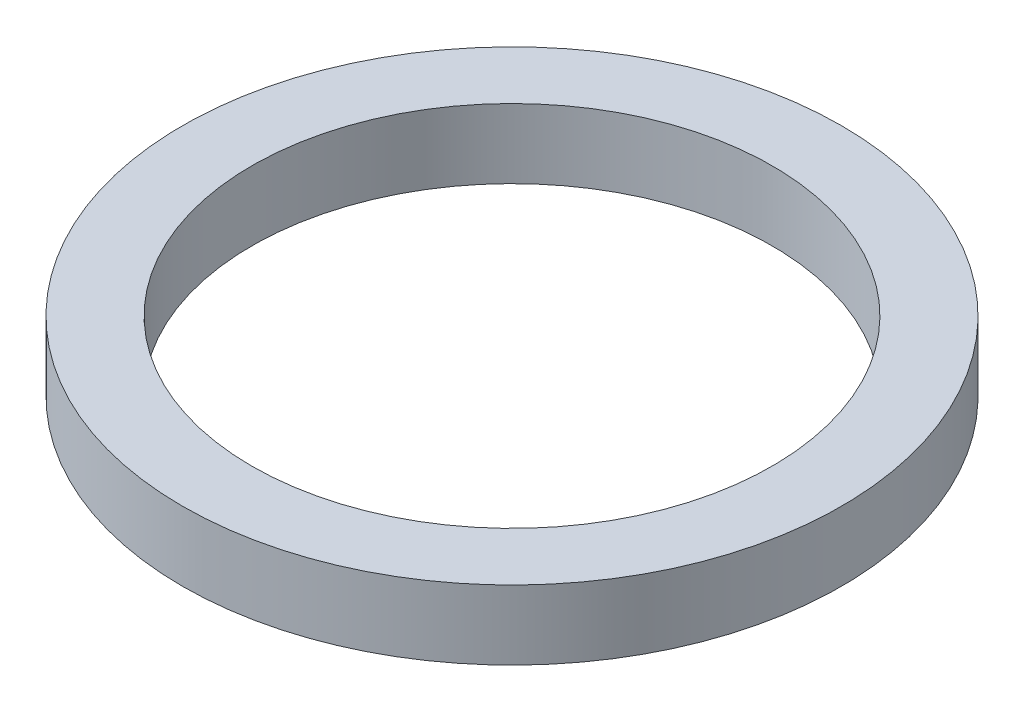
SolidWorks part; units mm, degrees
ref_plane "Front Plane" through (0, 0, 0) normal (0, 0, 1) x (1, 0, 0)
ref_plane "Top Plane" through (0, 0, 0) normal (0, 1, 0) x (1, 0, 0)
ref_plane "Right Plane" through (0, 0, 0) normal (1, 0, 0) x (0, 0, -1)
sketch "Sketch1" plane through (0, 0, 0) normal (0, 1, 0) x (1, 0, 0)
  circle A0 centre (0, 0) radius 7.5
  circle A1 centre (0, 0) radius 9.5
  dimension "D1" = 15
  dimension "D2" = 2
extrude "Boss-Extrude1" add sketch "Sketch1" along normal blind 2
